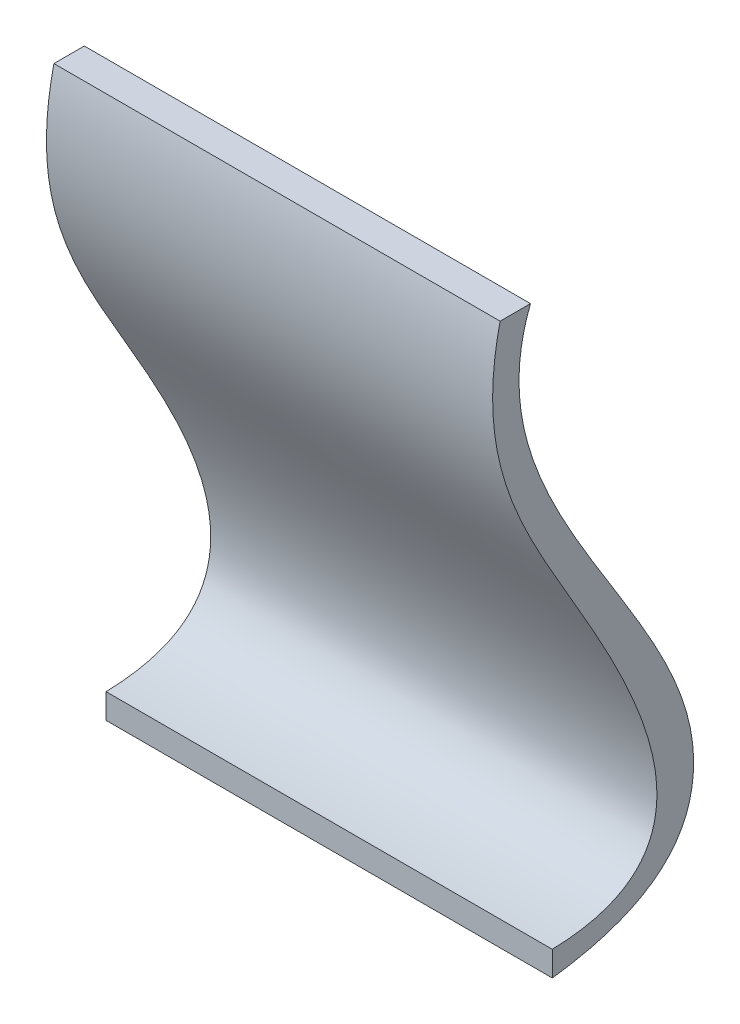
SolidWorks part; units mm, degrees
ref_plane "Plano frontal" through (0, 0, 0) normal (0, 0, 1) x (1, 0, 0)
ref_plane "Plano superior" through (0, 0, 0) normal (0, 1, 0) x (1, 0, 0)
ref_plane "Plano direito" through (0, 0, 0) normal (1, 0, 0) x (0, 0, -1)
sketch "Esboço1" plane through (0, 0, 0) normal (1, 0, 0) x (0, 0, -1)
  line L0 (0, 0) -> (0, 0.1673)
  line L1 (-0.3508, 4) -> (-0.1464, 4)
  line L2 (0, 0.1673) -> (0, 0)
  spline S0 degree 3 poles (0, 0) (0.7092, 0.0887) (1.5636, 1.3029) (-0.5931, 2.8708) (-0.1464, 4) knots 0 0 0 0 0.24093 1 1 1 1
  spline S1 degree 3 poles (0, 0.1673) (1.0007, 0.1923) (0.3824, 2.0661) (-0.5702, 3.0494) (-0.3508, 4) knots 0 0 0 0 0.429244 1 1 1 1
extrude "Ressalto-extrusão1" add sketch "Esboço1" along normal blind 3 contours S1 L0 S0 L1
